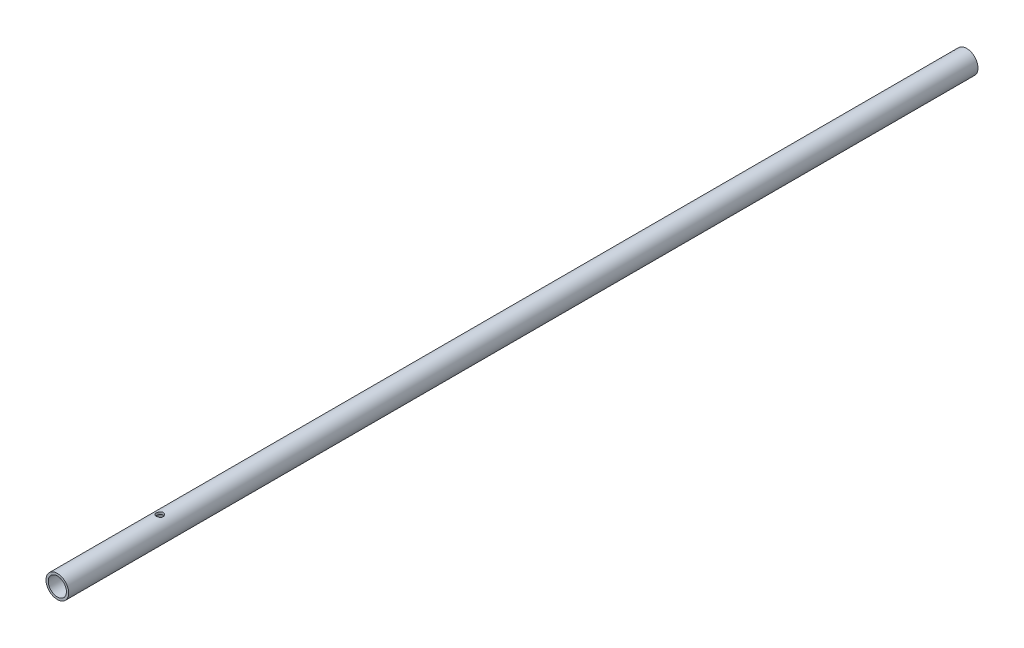
SolidWorks part; units mm, degrees
material "Thornel Mat VMA"
ref_plane "前视基准面" through (0, 0, 0) normal (0, 0, 1) x (1, 0, 0)
ref_plane "上视基准面" through (0, 0, 0) normal (0, 1, 0) x (1, 0, 0)
ref_plane "右视基准面" through (0, 0, 0) normal (1, 0, 0) x (0, 0, -1)
other "Configuration Table"
sketch "草图1" plane through (0, 0, 0) normal (0, 0, 1) x (1, 0, 0)
  circle A0 centre (0, 0) radius 5
  circle A1 centre (0, 0) radius 4
  dimension "D1" = 10
  dimension "D2" = 1
extrude "凸台-拉伸1" add sketch "草图1" along normal blind 400
sketch "草图2" plane through (0, 0, 0) normal (0, 1, 0) x (1, 0, 0)
  circle A0 centre (0, -31.3344) radius 1.5
  dimension "D1" = 3
  dimension "D2" = 31.3344
extrude "切除-拉伸1" cut sketch "草图2" against normal through all
sketch "草图3" plane through (0, 0, 0) normal (0, 1, 0) x (1, 0, 0)
  circle A0 centre (0, -355) radius 1.5
  dimension "D1" = 3
extrude "切除-拉伸2" cut sketch "草图3" along normal through all
